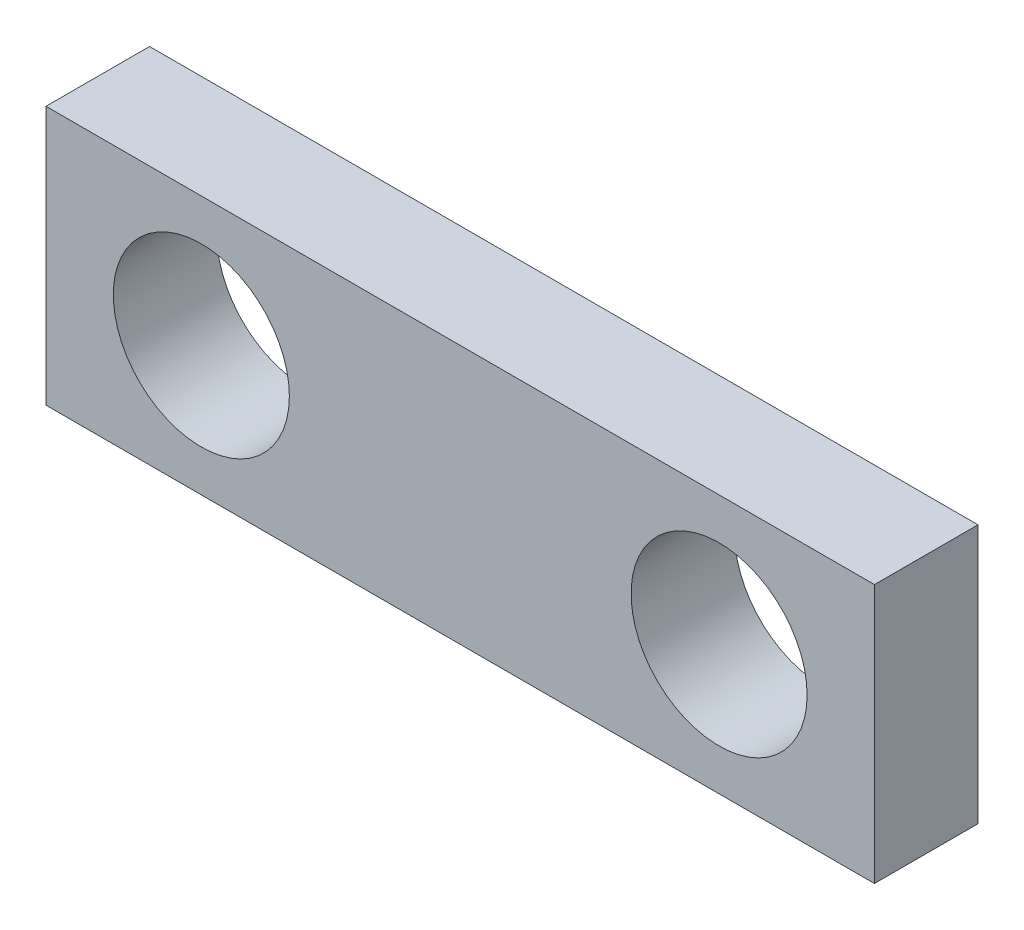
SolidWorks part; units mm, degrees
ref_plane "Ebene vorne" through (0, 0, 0) normal (0, 0, 1) x (1, 0, 0)
ref_plane "Ebene oben" through (0, 0, 0) normal (0, 1, 0) x (1, 0, 0)
ref_plane "Ebene rechts" through (0, 0, 0) normal (1, 0, 0) x (0, 0, -1)
sketch "Skizze1" plane through (0, 0, 0) normal (0, 0, 1) x (1, 0, 0)
  line L1 (0, 0) -> (16, 0)
  line L2 (0, 0) -> (0, 5)
  line L3 (0, 5) -> (16, 5)
  line L4 (16, 0) -> (16, 5)
  dimension "D1" = 16
  dimension "D2" = 5
extrude "Aufsatz-Linear austragen1" add sketch "Skizze1" along normal blind 2
hole_wizard "Durchgangsloch für M31" positions "Skizze2" profile "Skizze3" hole size "M3" standard "DIN" end condition up to next
sketch "Skizze2" plane through (0, 0, 2) normal (0, 0, 1) x (1, 0, 0)
  line L0 (0, 0) -> (16, 0) construction
  line L1 (16, 0) -> (16, 5) construction
  line L2 (0, 5) -> (0, 0) construction
  point P0 (3, 2.5)
  point P2 (13, 2.5)
  dimension "D1" = 2.5
  dimension "D2" = 2.5
  dimension "D3" = 3
  dimension "D4" = 3
sketch "Skizze3" plane through (3, 2.5, 2) normal (1, 0, 0) x (0, -1, 0)
  line L0 (0, 0) -> (0, 2)
  line L1 (0, 2) -> (1.7, 2)
  line L2 (1.7, 2) -> (1.7, 0)
  line L5 (1.7, 0) -> (0, 0)
  line L11 (0, -6.35) -> (0, 107.95) construction
  dimension "Bohrerdurchmesser" = 3.4
  dimension "Bohrungstiefe" = 2
